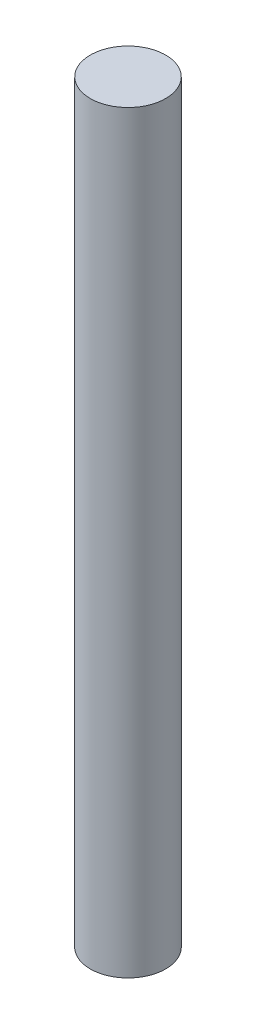
SolidWorks part; units mm, degrees
material "6061 Alloy"
ref_plane "Front Plane" through (0, 0, 0) normal (0, 0, 1) x (1, 0, 0)
ref_plane "Top Plane" through (0, 0, 0) normal (0, 1, 0) x (1, 0, 0)
ref_plane "Right Plane" through (0, 0, 0) normal (1, 0, 0) x (0, 0, -1)
sketch "Sketch1" plane through (0, 0, 0) normal (0, 1, 0) x (1, 0, 0)
  circle A1 centre (0, 0) radius 2.5
  dimension "D2" = 5
extrude "Boss-Extrude2" add sketch "Sketch1" along normal blind 50
